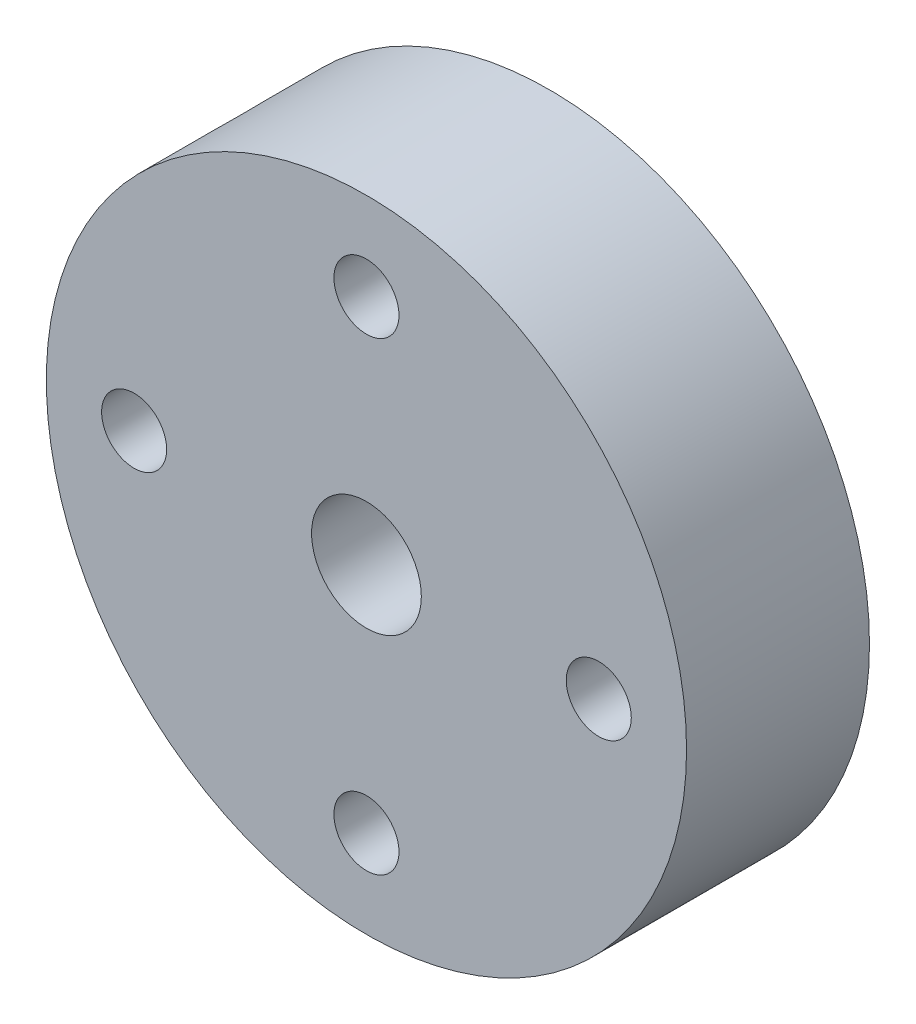
SolidWorks part; units mm, degrees
material "6061-T6 (SS)"
ref_plane "Front Plane" through (0, 0, 0) normal (0, 0, 1) x (1, 0, 0)
ref_plane "Top Plane" through (0, 0, 0) normal (0, 1, 0) x (1, 0, 0)
ref_plane "Right Plane" through (0, 0, 0) normal (1, 0, 0) x (0, 0, -1)
sketch "Sketch1" plane through (0, 0, 0) normal (0, 0, 1) x (1, 0, 0)
  circle A0 centre (0, 0) radius 8.75
  circle A1 centre (0, 0) radius 1.5
  dimension "D1" = 17.5
  dimension "D2" = 3
extrude "Boss-Extrude1" add sketch "Sketch1" along normal blind 5
sketch "Sketch2" plane through (0, 0, 5) normal (0, 0, 1) x (1, 0, 0)
  line L0 (0, -6.35) -> (0, 6.35) construction
  line L1 (6.35, 0) -> (-6.35, 0) construction
  point P6 (0, 0)
  dimension "D1" = 6.35
  dimension "D2" = 6.35
hole_wizard "#2-56 Tapped Hole1" positions "Sketch4" profile "Sketch3" tap size "#2-56" standard "ANSI Inch" end condition through all
sketch "Sketch4" plane through (0, 0, 5) normal (0, 0, 1) x (1, 0, 0)
  point P0 (-6.35, 0)
  point P3 (0, 6.35)
  point P7 (6.35, 0)
  point P10 (0, -6.35)
sketch "Sketch3" plane through (-6.35, 0, 5) normal (1, 0, 0) x (0, -1, 0)
  line L0 (0, 0) -> (0, 5)
  line L1 (0, 5) -> (0.889, 5)
  line L2 (0.889, 5) -> (0.889, 0)
  line L5 (0.889, 0) -> (0, 0)
  line L11 (0, -6.35) -> (0, 107.95) construction
  dimension "Thru Tap Drill Dia." = 1.778
  dimension "Thru Tap Drill Depth" = 5
cosmetic thread "Hole Thread1"
cosmetic thread "Hole Thread2"
cosmetic thread "Hole Thread3"
cosmetic thread "Hole Thread4"
hole_wizard "#4-40 Tapped Hole1" positions "3DSketch1" profile "Sketch5" tap size "#4-40" standard "ANSI Inch"
sketch3d "3DSketch1"
  point P0 (-6.7597, 5.556, 2.4086)
sketch "Sketch5" plane through (-6.7597, 5.556, 2.4086) normal (0, 0, 1) x (-0.635, -0.7725, 0)
  line L0 (0, 0) -> (0, 8.2992)
  line L1 (0, 8.2992) -> (1.1303, 7.62)
  line L2 (1.1303, 7.62) -> (1.1303, 0)
  line L5 (1.1303, 0) -> (0, 0)
  line L10 (0, 8.2992) -> (-1.1303, 7.62) construction
  line L11 (0, -6.35) -> (0, 107.95) construction
  dimension "Tap Drill Dia." = 2.2606
  dimension "Tap Drill Depth" = 7.62
  dimension "Drill Angle" = 118
cosmetic thread "Hole Thread5"
